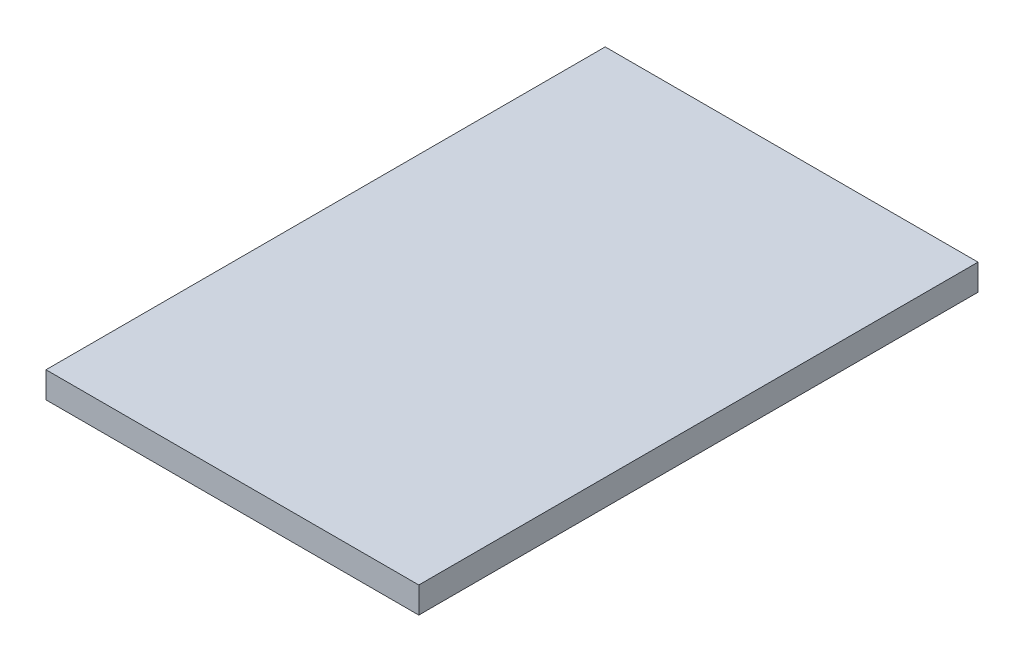
SolidWorks part; units mm, degrees
ref_plane "Alzado" through (0, 0, 0) normal (0, 0, 1) x (1, 0, 0)
ref_plane "Planta" through (0, 0, 0) normal (0, 1, 0) x (1, 0, 0)
ref_plane "Vista lateral" through (0, 0, 0) normal (1, 0, 0) x (0, 0, -1)
ref_plane "Plano4" through (0, -0.7, 0) normal (0, -1, 0) x (1, 0, 0)
sketch "Croquis1" plane through (0, -0.7, 0) normal (0, -1, 0) x (1, 0, 0)
  line L0 (0, 7.5) -> (0, -7.5)
  line L1 (0, -7.5) -> (10, -7.5)
  line L2 (10, -7.5) -> (10, 7.5)
  line L3 (10, 7.5) -> (0, 7.5)
extrude "Saliente-Extruir1" add sketch "Croquis1" against normal blind 0.7
